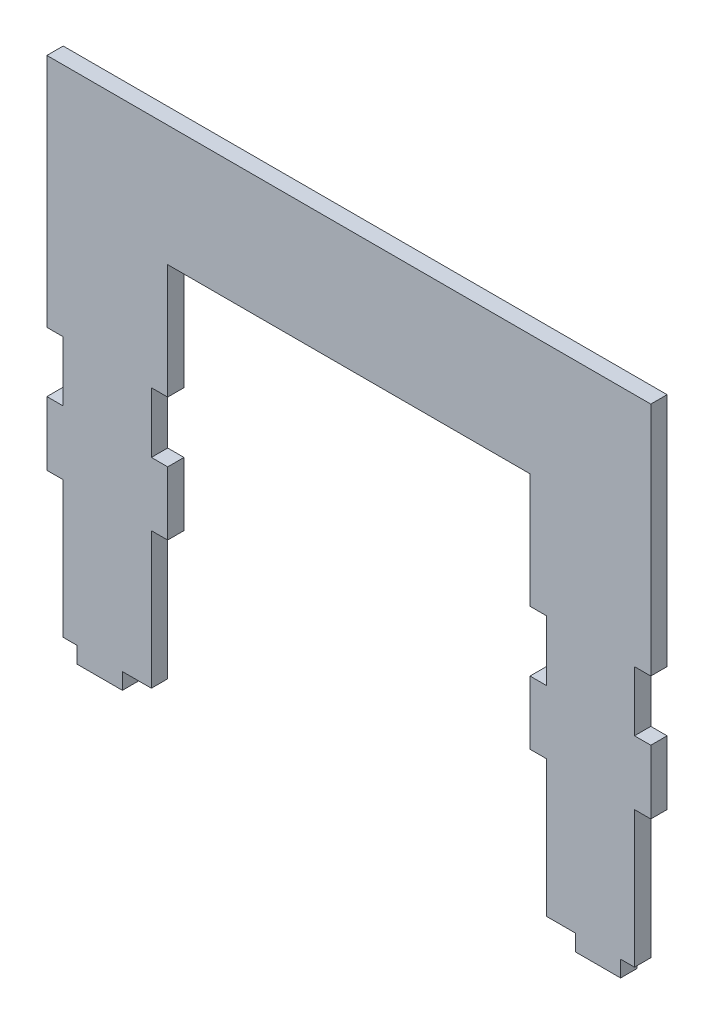
SolidWorks part; units mm, degrees
ref_plane "Front Plane" through (0, 0, 0) normal (0, 0, 1) x (1, 0, 0)
ref_plane "Top Plane" through (0, 0, 0) normal (0, 1, 0) x (1, 0, 0)
ref_plane "Right Plane" through (0, 0, 0) normal (1, 0, 0) x (0, 0, -1)
sketch "Sketch1" plane through (0, 0, 0) normal (0, 0, 1) x (1, 0, 0)
  line L0 (-32.7, -12.6026) -> (-32.7, 10)
  line L1 (-32.7, 10) -> (-30, 10)
  line L2 (-30, 10) -> (-30, 20.5)
  line L3 (-30, 20.5) -> (-32.7, 20.5)
  line L4 (-32.7, 20.5) -> (-32.7, 30.5)
  line L5 (-32.7, 30.5) -> (-30, 30.5)
  line L6 (-30, 30.5) -> (-30, 49.5)
  line L7 (-50, 69.5) -> (50, 69.5)
  line L8 (0, 49.5) -> (0, 0) construction
  line L9 (-32.7, -12.6026) -> (-37.5, -12.6026)
  line L10 (-37.5, -12.6026) -> (-37.5, -15.3026)
  line L11 (-37.5, -15.3026) -> (-45, -15.3026)
  line L12 (-45, -15.3026) -> (-45, -12.6026)
  line L13 (-45, -12.6026) -> (-47.3, -12.6026)
  line L14 (-50, 20.5792) -> (-50, 10)
  line L15 (-30, 49.5) -> (30, 49.5)
  line L16 (-30, 10) -> (-30, -12.6026) construction
  line L17 (45, -12.6026) -> (47.3, -12.6026)
  line L18 (-47.3, 20.5792) -> (-50, 20.5792)
  line L19 (-47.3, 20.5792) -> (-47.3, 30.5)
  line L20 (-47.3, 30.5) -> (-50, 30.5)
  line L21 (47.3, 10) -> (47.3, -12.6026)
  line L22 (-50, 10) -> (-47.3, 10)
  line L23 (50, 10) -> (47.3, 10)
  line L24 (50, 20.5792) -> (50, 10)
  line L25 (47.3, 20.5792) -> (50, 20.5792)
  line L26 (45, -15.3026) -> (45, -12.6026)
  line L27 (37.5, -15.3026) -> (45, -15.3026)
  line L28 (37.5, -12.6026) -> (37.5, -15.3026)
  line L29 (32.7, -12.6026) -> (37.5, -12.6026)
  line L30 (30, 30.5) -> (30, 49.5)
  line L31 (32.7, 30.5) -> (30, 30.5)
  line L32 (32.7, 20.5) -> (32.7, 30.5)
  line L33 (30, 20.5) -> (32.7, 20.5)
  line L34 (30, 10) -> (30, 20.5)
  line L35 (32.7, 10) -> (30, 10)
  line L36 (32.7, -12.6026) -> (32.7, 10)
  line L37 (47.3, 20.5792) -> (47.3, 30.5)
  line L38 (-47.3, 10) -> (-47.3, -12.6026)
  line L39 (47.3, 30.5) -> (50, 30.5)
  line L40 (-50, 30.5) -> (-50, 69.5)
  line L43 (50, 30.5) -> (50, 69.5)
  point P20 (0, 69.5)
  point P26 (0, 69.5)
  dimension "D1" = 2.7
  dimension "D2" = 30
  dimension "D3" = 2.7
  dimension "D4" = 10
  dimension "D6" = 19
  dimension "D7" = 20
  dimension "D11" = 7.5
extrude "Base" add sketch "Sketch1" along normal blind 2.7
